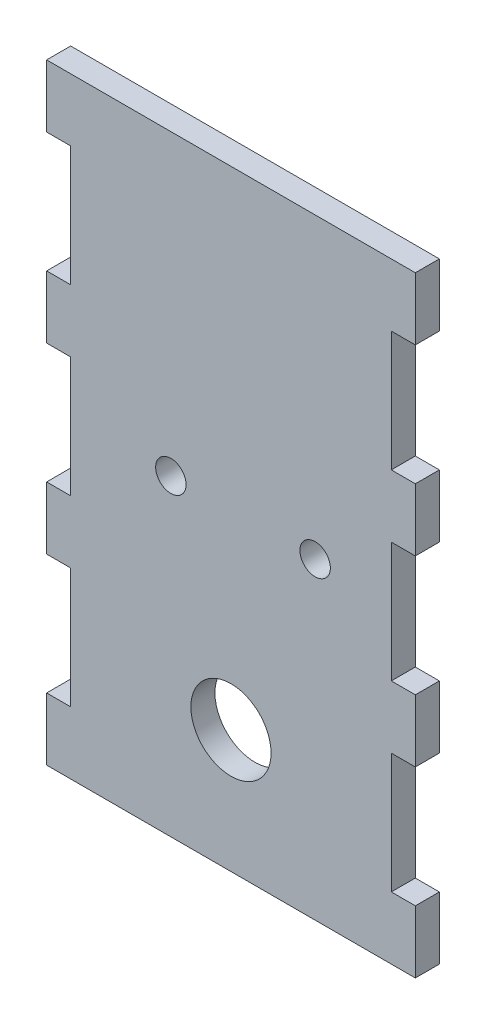
SolidWorks part; units mm, degrees
material "Oak"
ref_plane "Front Plane" through (0, 0, 0) normal (0, 0, 1) x (1, 0, 0)
ref_plane "Top Plane" through (0, 0, 0) normal (0, 1, 0) x (1, 0, 0)
ref_plane "Right Plane" through (0, 0, 0) normal (1, 0, 0) x (0, 0, -1)
sketch "Sketch1" plane through (0, 0, 0) normal (0, 0, 1) x (1, 0, 0)
  line L1 (-40.9935, 16.542) -> (5.0065, 16.542)
  line L2 (-40.9935, 16.542) -> (-40.9935, -59.658)
  line L3 (-40.9935, -59.658) -> (5.0065, -59.658)
  line L4 (5.0065, 16.542) -> (5.0065, -59.658)
  dimension "D1" = 76.2
  dimension "D2" = 46
extrude "Boss-Extrude1" add sketch "Sketch1" along normal blind 3
sketch "Sketch2" plane through (0, 0, 3) normal (0, 0, 1) x (1, 0, 0)
  line L0 (-40.9935, 16.542) -> (-40.9935, -59.658) construction
  line L1 (-40.9935, 8.742) -> (-37.9935, 8.742)
  line L2 (-40.9935, 8.742) -> (-40.9935, -6.258)
  line L3 (-40.9935, -6.258) -> (-37.9935, -6.258)
  line L4 (-37.9935, 8.742) -> (-37.9935, -6.258)
  line L5 (5.0065, 16.542) -> (-40.9935, 16.542) construction
  line L6 (5.0065, -59.658) -> (5.0065, 16.542) construction
  line L7 (5.0065, 8.742) -> (2.0065, 8.742)
  line L8 (5.0065, 8.742) -> (5.0065, -6.258)
  line L9 (5.0065, -6.258) -> (2.0065, -6.258)
  line L10 (2.0065, 8.742) -> (2.0065, -6.258)
  point P8 (-39.4935, 8.742)
  dimension "D1" = 3
  dimension "D2" = 7.8
  dimension "D3" = 15
  dimension "D4" = 3
  dimension "D5" = 7.8
  dimension "D6" = 15
extrude "Cut-Extrude1" cut sketch "Sketch2" against normal through all
pattern_linear "LPattern1" count 3 spacing 22.8 along (0, -1, 0) of "Cut-Extrude1"
hole_wizard "#6 Clearance Hole1" positions "Sketch3" profile "Sketch4" hole size "#6" standard "ANSI Inch" end condition through all
sketch "Sketch3" plane through (0, 0, 3) normal (0, 0, 1) x (1, 0, 0)
  point P0 (-25.4935, -20.658)
  point P3 (-7.4935, -20.658)
sketch "Sketch4" plane through (-25.4935, -20.658, 3) normal (1, 0, 0) x (0, -1, 0)
  line L0 (0, 0) -> (0, 3)
  line L1 (0, 3) -> (1.8986, 3)
  line L2 (1.8986, 3) -> (1.8986, 0)
  line L5 (1.8986, 0) -> (0, 0)
  line L11 (0, -6.35) -> (0, 107.95) construction
  dimension "Thru Hole Dia." = 3.7973
  dimension "Thru Hole Depth" = 3
sketch "Sketch5" plane through (0, 0, 0) normal (0, 0, -1) x (-1, 0, 0)
  line L0 (40.9935, -59.658) -> (-5.0065, -59.658) construction
  line L1 (-2.0065, -36.858) -> (-2.0065, -51.858) construction
  circle A0 centre (17.9935, -44.358) radius 5
  point P5 (17.9935, -59.658)
  point P8 (-2.0065, -44.358)
  dimension "D1" = 10
extrude "Cut-Extrude2" cut sketch "Sketch5" against normal up to next
